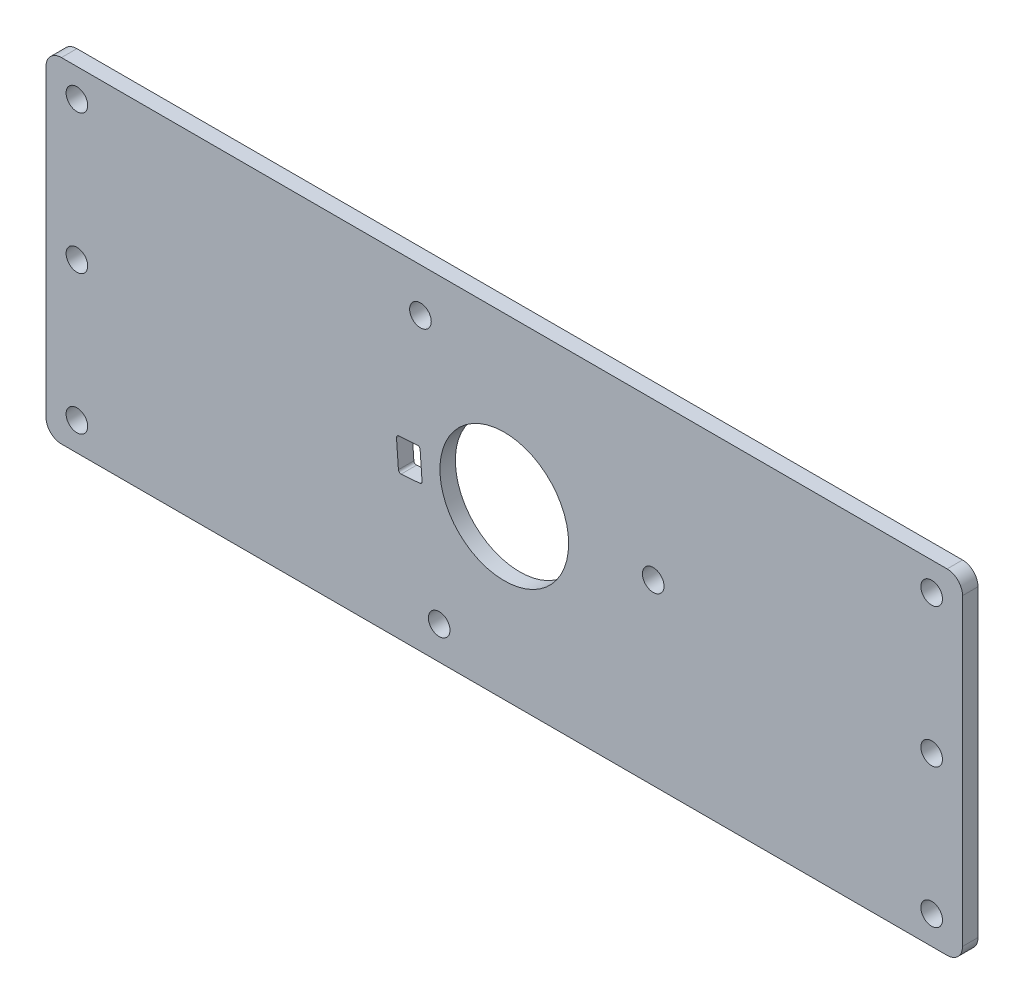
SolidWorks part; units mm, degrees
material "Thornel Mat VMA"
ref_plane "前视基准面" through (0, 0, 0) normal (0, 0, 1) x (1, 0, 0)
ref_plane "上视基准面" through (0, 0, 0) normal (0, 1, 0) x (1, 0, 0)
ref_plane "右视基准面" through (0, 0, 0) normal (1, 0, 0) x (0, 0, -1)
other "Configuration Table"
sketch "草图1" plane through (0, 0, 0) normal (0, 0, 1) x (1, 0, 0)
  line L1 (89, -32.5) -> (-89, -32.5)
  line L2 (89, -32.5) -> (89, 32.5)
  line L3 (89, 32.5) -> (-89, 32.5)
  line L4 (-89, -32.5) -> (-89, 32.5)
  line L5 (89, -32.5) -> (-89, 32.5) construction
  line L6 (89, 32.5) -> (-89, -32.5) construction
  point P0 (0, 0)
  dimension "D1" = 65
  dimension "D2" = 178
extrude "凸台-拉伸1" add sketch "草图1" along normal blind 3
fillet "圆角1" radius 3 4 edges at (89, 32.5, 1.5) (89, -32.5, 1.5) (-89, -32.5, 1.5) (-89, 32.5, 1.5)
sketch "草图2" plane through (0, 0, 3) normal (0, 0, 1) x (1, 0, 0)
  line L0 (0, 32.5) -> (0, -32.5) construction
  line L1 (86, 32.5) -> (-86, 32.5) construction
  line L2 (-86, -32.5) -> (86, -32.5) construction
  line L3 (-89, 0) -> (89, 0) construction
  line L4 (-89, 29.5) -> (-89, -29.5) construction
  line L5 (89, -29.5) -> (89, 29.5) construction
  line L6 (-83, 32.5) -> (-83, -32.5) construction
  line L7 (83, 32.5) -> (83, -32.5) construction
  circle A0 centre (-83, 0) radius 2.1
  circle A1 centre (-83, 27) radius 2.1
  circle A2 centre (-83, -27) radius 2.1
  circle A3 centre (83, -27) radius 2.1
  circle A4 centre (83, 27) radius 2.1
  circle A5 centre (83, 0) radius 2.1
  circle A6 centre (0, 0) radius 12.5
  circle A7 centre (-16.2806, 23.9988) radius 2.1
  circle A8 centre (28.9239, 2.1) radius 2.1
  circle A9 centre (-12.6433, -26.0988) radius 2.1
  line B0 (-20.0222, -4.5619) -> (-16.4317, -4.3012)
  line B1 (-20.9337, 1.087) -> (-20.5571, -4.0994)
  line B2 (-16.8806, 1.8826) -> (-20.4712, 1.6219)
  line B3 (-15.9692, -3.7663) -> (-16.3457, 1.4201)
  circle B4 centre (0, 0) radius 11
  circle B5 centre (-16.2806, 23.9988) radius 1.8
  circle B6 centre (28.9239, 2.1) radius 1.8
  circle B7 centre (-12.6433, -26.0988) radius 2.1
  arc B8 (-16.4317, -4.3012) -> (-15.9692, -3.7663) centre (-16.4679, -3.8025) ccw
  arc B9 (-20.5571, -4.0994) -> (-20.0222, -4.5619) centre (-20.0584, -4.0632) ccw
  arc B10 (-20.4712, 1.6219) -> (-20.9337, 1.087) centre (-20.435, 1.1232) ccw
  arc B11 (-16.4307, 1.6646) -> (-16.8806, 1.8826) centre (-16.8444, 1.3839) ccw
  arc B12 (-16.3457, 1.4201) -> (-16.4307, 1.6646) centre (-16.8444, 1.3839) ccw
  dimension "D1" = 4.2
  dimension "D2" = 27
  dimension "D3" = 27
  dimension "D5" = 25
  dimension "D6" = 4.2
  dimension "D4" = 6
sketch_block_instance "块1-1"
sketch_block "块1"
extrude "切除-拉伸1" cut sketch "草图2" against normal blind 10 contours A1 | A0 | A2 | B4 | A6 B4 | A7 B5 | B5 | A8 B6 | B6 | A9 | B3 B12 B11 B2 B10 B1 B9 B0 B8 | A4 | A5 | A3
